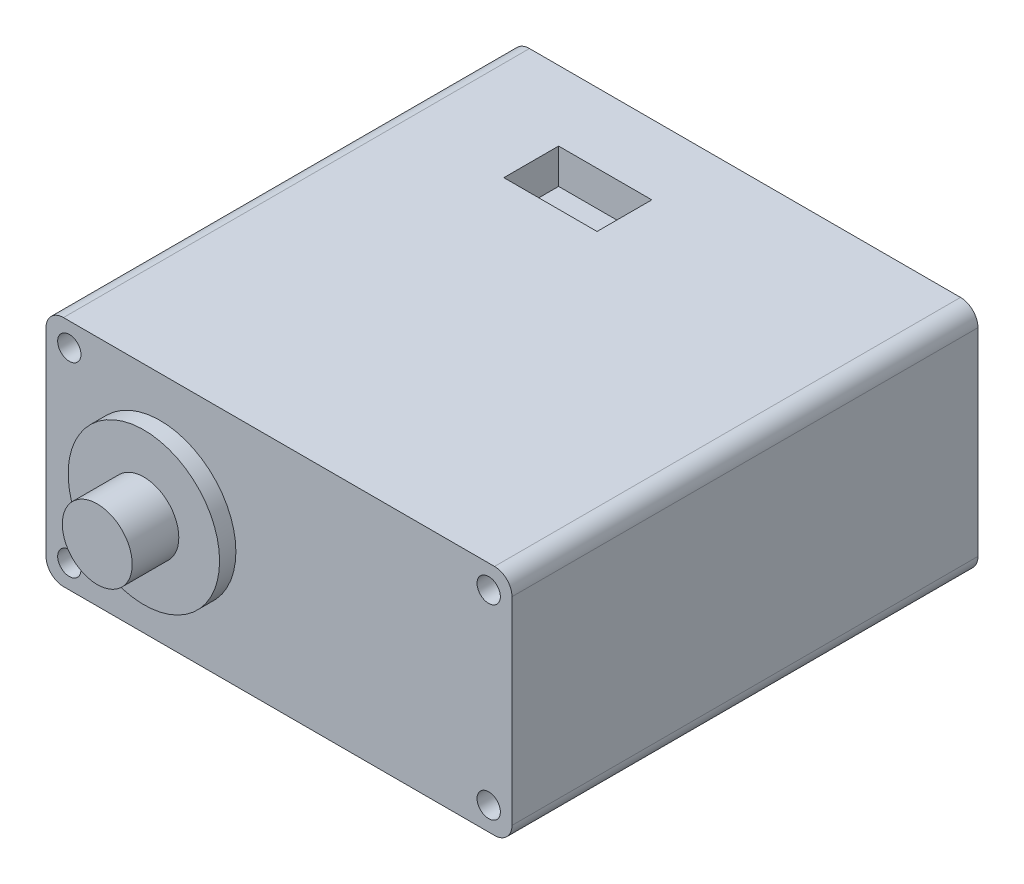
SolidWorks part; units mm, degrees
ref_plane "前视基准面" through (0, 0, 0) normal (0, 0, 1) x (1, 0, 0)
ref_plane "上视基准面" through (0, 0, 0) normal (0, 1, 0) x (1, 0, 0)
ref_plane "右视基准面" through (0, 0, 0) normal (1, 0, 0) x (0, 0, -1)
other "Configuration Table"
sketch "草图1" plane through (0, 0, 0) normal (0, 0, 1) x (1, 0, 0)
  line L1 (-16.5753, 100.529) -> (-56.5753, 100.529)
  line L2 (-16.5753, 100.529) -> (-16.5753, 120.529)
  line L3 (-16.5753, 120.529) -> (-56.5753, 120.529)
  line L4 (-56.5753, 100.529) -> (-56.5753, 120.529)
  circle A0 centre (-54.5753, 118.529) radius 1
  circle A1 centre (-54.5753, 102.529) radius 1
  circle A2 centre (-18.5753, 102.529) radius 1
  circle A3 centre (-18.5753, 118.529) radius 1
  dimension "D3" = 2
  dimension "D1" = 40
  dimension "D2" = 20
  dimension "D4" = 2
  dimension "D5" = 2
  dimension "D6" = 2
  dimension "D7" = 2
extrude "凸台-拉伸1" add sketch "草图1" along normal blind 40
fillet "圆角1" radius 1.5 4 edges at (-56.5753, 120.529, 20) (-16.5753, 120.529, 20) (-16.5753, 100.529, 20) (-56.5753, 100.529, 20)
sketch "草图2" plane through (0, 0, 40) normal (0, 0, 1) x (1, 0, 0)
  line L0 (-56.5753, 110.529) -> (-16.5753, 110.529) construction
  line L4 (-18.0753, 120.529) -> (-55.0753, 120.529)
  line L5 (-56.5753, 119.029) -> (-56.5753, 102.029)
  line L6 (-55.0753, 100.529) -> (-18.0753, 100.529)
  line L7 (-16.5753, 102.029) -> (-16.5753, 119.029)
  line L8 (-18.0753, 120.529) -> (-55.0753, 120.529)
  line L9 (-56.5753, 119.029) -> (-56.5753, 102.029)
  line L10 (-55.0753, 100.529) -> (-18.0753, 100.529)
  line L11 (-16.5753, 102.029) -> (-16.5753, 119.029)
  circle A0 centre (-46.7753, 110.529) radius 9.75
  arc A4 (-55.0753, 120.529) -> (-56.5753, 119.029) centre (-55.0753, 119.029) ccw
  arc A5 (-56.5753, 102.029) -> (-55.0753, 100.529) centre (-55.0753, 102.029) ccw
  arc A6 (-18.0753, 100.529) -> (-16.5753, 102.029) centre (-18.0753, 102.029) ccw
  arc A7 (-16.5753, 119.029) -> (-18.0753, 120.529) centre (-18.0753, 119.029) ccw
  arc A8 (-55.0753, 120.529) -> (-56.5753, 119.029) centre (-55.0753, 119.029) ccw
  arc A9 (-56.5753, 102.029) -> (-55.0753, 100.529) centre (-55.0753, 102.029) ccw
  arc A10 (-18.0753, 100.529) -> (-16.5753, 102.029) centre (-18.0753, 102.029) ccw
  arc A11 (-16.5753, 119.029) -> (-18.0753, 120.529) centre (-18.0753, 119.029) ccw
  dimension "D2" = 19.5
  dimension "D3" = 9.8
  dimension "D1" = 0
sketch "草图3" plane through (0, 0, 40) normal (0, 0, 1) x (1, 0, 0)
  circle A0 centre (-46.7753, 110.529) radius 6.5
  dimension "D2" = 13
extrude "凸台-拉伸3" add sketch "草图3" along direction (0, 0, 1) on the side of the normal blind 1.4 contours A0
sketch "草图4" plane through (0, 0, 0) normal (0, 0, -1) x (-1, 0, 0)
  circle A0 centre (46.7753, 110.529) radius 6.5 construction
  circle A1 centre (46.7753, 110.529) radius 9.75
  circle A2 centre (46.7753, 110.529) radius 9.75
  circle A3 centre (46.7753, 110.529) radius 6.5
  dimension "D1" = 0
extrude "凸台-拉伸4" add sketch "草图4" along normal blind 1.4 contours A3
sketch "草图6" plane through (0, 0, 41.4) normal (0, 0, 1) x (1, 0, 0)
  circle A0 centre (-46.7753, 110.529) radius 3
  circle A1 centre (-46.7753, 110.529) radius 9.75
  circle A2 centre (-46.7753, 110.529) radius 9.75
  dimension "D2" = 6
  dimension "D1" = 0
extrude "凸台-拉伸6" add sketch "草图6" along normal blind 4 contours A0
sketch "草图7" plane through (0, 100.529, 0) normal (0, -1, 0) x (1, 0, 0)
  line L0 (-55.0753, 0) -> (-18.0753, 0) construction
  line L1 (-46.5753, 10.7) -> (-38.5753, 10.7)
  line L2 (-46.5753, 10.7) -> (-46.5753, 6)
  line L3 (-46.5753, 6) -> (-38.5753, 6)
  line L4 (-38.5753, 10.7) -> (-38.5753, 6)
  line L5 (-46.5753, 10.7) -> (-38.5753, 6) construction
  line L6 (-46.5753, 6) -> (-38.5753, 10.7) construction
  line L9 (-56.5753, 0) -> (-56.5753, 40) construction
  point P0 (-42.5753, 8.35)
  dimension "D1" = 6
  dimension "D2" = 4.7
  dimension "D3" = 10
  dimension "D4" = 8
extrude "切除-拉伸1" cut sketch "草图7" against normal blind 3
ref_plane "基准面1" through (0, 110.529, 0) normal (0, -1, 0) x (-1, 0, 0)
mirror "镜向1" about plane through (0, 110.529, 0) normal (0, -1, 0) of "切除-拉伸1"
sketch "草图8" plane through (-56.5753, 0, 0) normal (-1, 0, 0) x (0, 0, 1)
  line L1 (6, 114.529) -> (10.7, 114.529)
  line L2 (6, 114.529) -> (6, 106.529)
  line L3 (6, 106.529) -> (10.7, 106.529)
  line L4 (10.7, 114.529) -> (10.7, 106.529)
  line L5 (6, 114.529) -> (10.7, 106.529) construction
  line L6 (6, 106.529) -> (10.7, 114.529) construction
  line L7 (0, 119.029) -> (0, 102.029) construction
  line L8 (-20.35, 110.529) -> (20.35, 110.529) construction
  point P0 (8.35, 110.529)
  dimension "D1" = 4.7
  dimension "D2" = 8
  dimension "D3" = 6
  dimension "D4" = 4
extrude "切除-拉伸2" cut sketch "草图8" against normal blind 3
